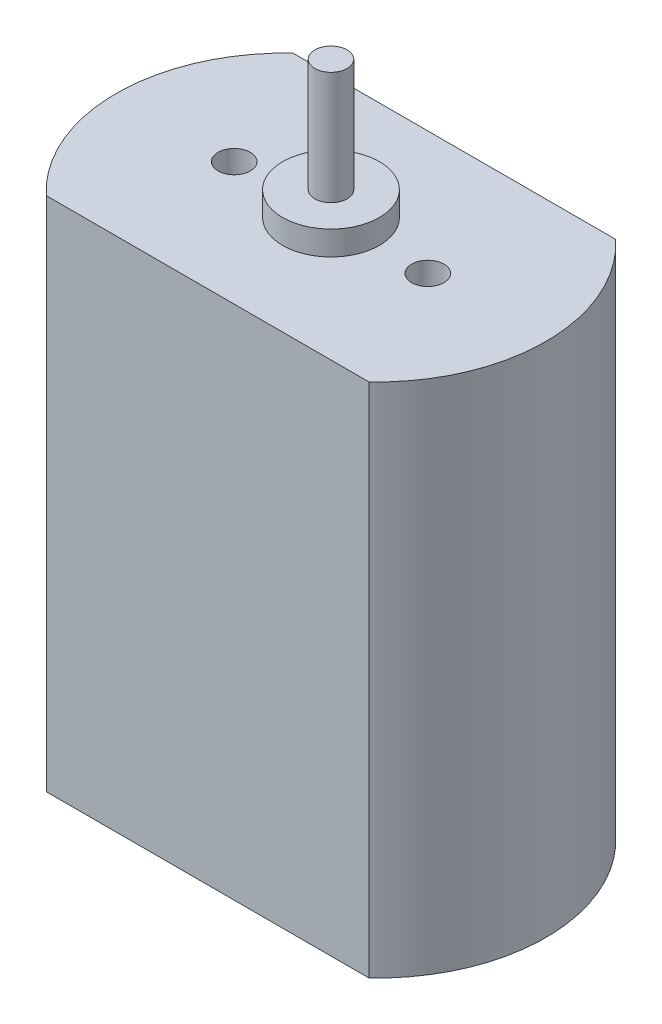
SolidWorks part; units mm, degrees
ref_plane "前视基准面" through (0, 0, 0) normal (0, 0, 1) x (1, 0, 0)
ref_plane "上视基准面" through (0, 0, 0) normal (0, 1, 0) x (1, 0, 0)
ref_plane "右视基准面" through (0, 0, 0) normal (1, 0, 0) x (0, 0, -1)
sketch "草图1" plane through (0, 0, 0) normal (0, 1, 0) x (1, 0, 0)
  line L0 (0, 0) -> (0, -10.0222) construction
  line L1 (-10, 7.65) -> (10, 7.65)
  line L3 (-10, -7.65) -> (10, -7.65)
  line L5 (-10, 7.65) -> (10, -7.65) construction
  line L6 (-10, -7.65) -> (10, 7.65) construction
  arc A1 (10, -7.65) -> (10, 7.65) centre (2.8403, 0) ccw
  arc A2 (-10, -7.65) -> (-10, 7.65) centre (-2.8403, 0) cw
  point P0 (0, 0)
  dimension "D1" = 20
  dimension "D2" = 15.3
extrude "凸台-拉伸1" add sketch "草图1" along normal blind 32
sketch "草图2" plane through (0, 32, 0) normal (0, 1, 0) x (1, 0, 0)
  circle A0 centre (0, 0) radius 3
  dimension "D1" = 6
extrude "凸台-拉伸2" add sketch "草图2" along normal blind 1.5
sketch "草图3" plane through (0, 32, 0) normal (0, 1, 0) x (1, 0, 0)
  circle A0 centre (-6, 0) radius 1
  circle A1 centre (6, 0) radius 1
  dimension "D1" = 2
  dimension "D2" = 6
  dimension "D3" = 2
  dimension "D4" = 6
extrude "切除-拉伸1" cut sketch "草图3" against normal blind 1.5
sketch "草图4" plane through (0, 33.5, 0) normal (0, 1, 0) x (1, 0, 0)
  circle A0 centre (0, 0) radius 1
  dimension "D1" = 2
extrude "凸台-拉伸3" add sketch "草图4" along normal blind 7
